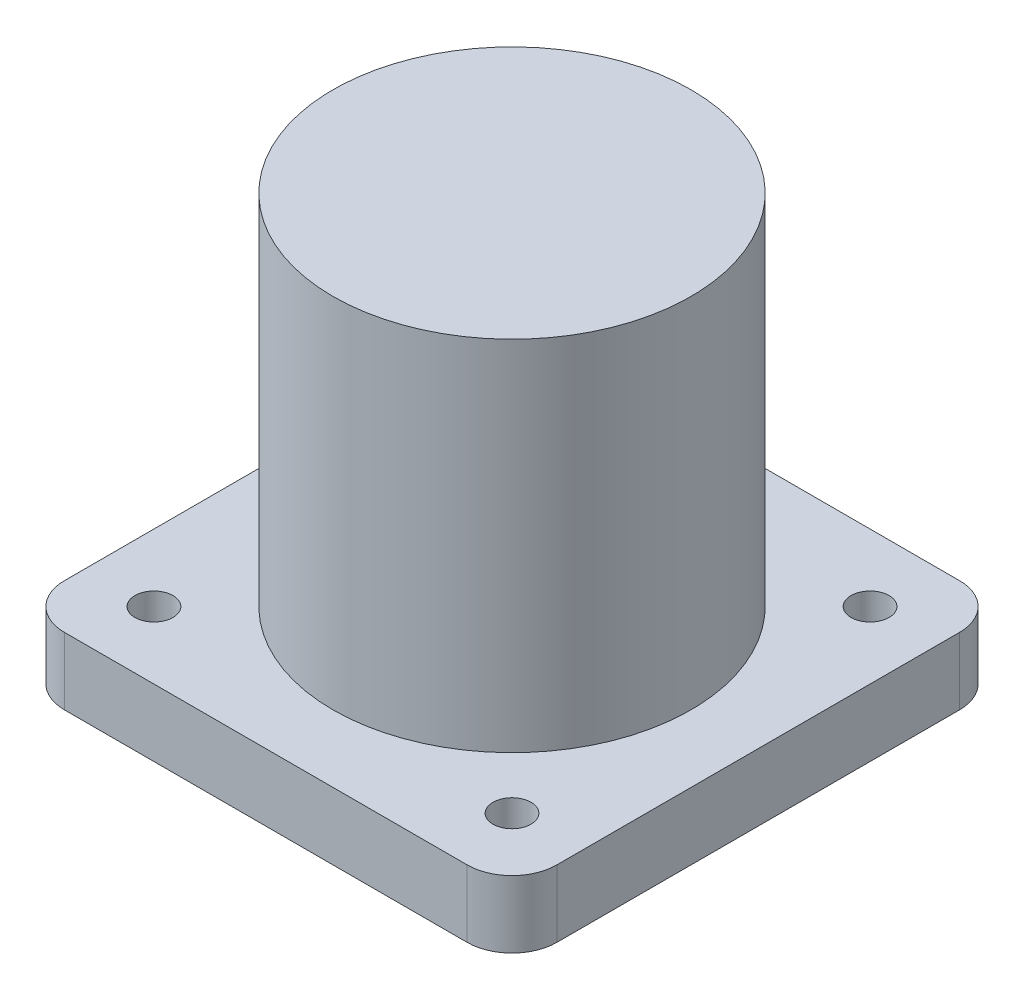
SolidWorks part; units mm, degrees
ref_plane "Front Plane" through (0, 0, 0) normal (0, 0, 1) x (1, 0, 0)
ref_plane "Top Plane" through (0, 0, 0) normal (0, 1, 0) x (1, 0, 0)
ref_plane "Right Plane" through (0, 0, 0) normal (1, 0, 0) x (0, 0, -1)
sketch "Sketch1" plane through (0, 0, 0) normal (0, 1, 0) x (1, 0, 0)
  line L1 (-43.7666, 29.6154) -> (66.2334, 29.6154)
  line L2 (-43.7666, 29.6154) -> (-43.7666, -80.3846)
  line L3 (-43.7666, -80.3846) -> (66.2334, -80.3846)
  line L4 (66.2334, 29.6154) -> (66.2334, -80.3846)
  dimension "D1" = 110
  dimension "D2" = 110
extrude "Boss-Extrude1" add sketch "Sketch1" along normal blind 15
sketch "Sketch3" plane through (0, 0, 0) normal (0, -1, 0) x (-1, 0, 0)
  line L0 (43.7666, -80.3846) -> (-66.2334, -80.3846) construction
  line L1 (-66.2334, -80.3846) -> (-66.2334, 29.6154) construction
  line L3 (-66.2334, 29.6154) -> (43.7666, 29.6154) construction
  line L4 (43.7666, 29.6154) -> (43.7666, -80.3846) construction
  circle A0 centre (28.7666, -65.3846) radius 4.25
  circle A1 centre (-51.2334, -65.3846) radius 4.25
  circle A2 centre (-51.2334, 14.6154) radius 4.25
  circle A3 centre (28.7666, 14.6154) radius 4.25
  dimension "D1" = 8.5
  dimension "D2" = 8.5
  dimension "D3" = 8.5
  dimension "D4" = 8.5
  dimension "D5" = 15
  dimension "D6" = 15
  dimension "D7" = 15
  dimension "D8" = 15
  dimension "D9" = 15
  dimension "D10" = 15
  dimension "D11" = 15
  dimension "D12" = 15
extrude "Cut-Extrude1" cut sketch "Sketch3" against normal blind 15
fillet "Fillet1" radius 10 4 edges at (-43.7666, 7.5, 80.3846) (66.2334, 7.5, 80.3846) (-43.7666, 7.5, -29.6154) (66.2334, 7.5, -29.6154)
sketch "Sketch4" plane through (0, 15, 0) normal (0, 1, 0) x (1, 0, 0)
  line L0 (66.2334, -70.3846) -> (66.2334, 19.6154) construction
  line L1 (56.2334, 29.6154) -> (-33.7666, 29.6154) construction
  circle A0 centre (11.2334, -25.3846) radius 40
  dimension "D1" = 80
  dimension "D2" = 55
  dimension "D3" = 55
extrude "Boss-Extrude2" add sketch "Sketch4" along normal blind 80
